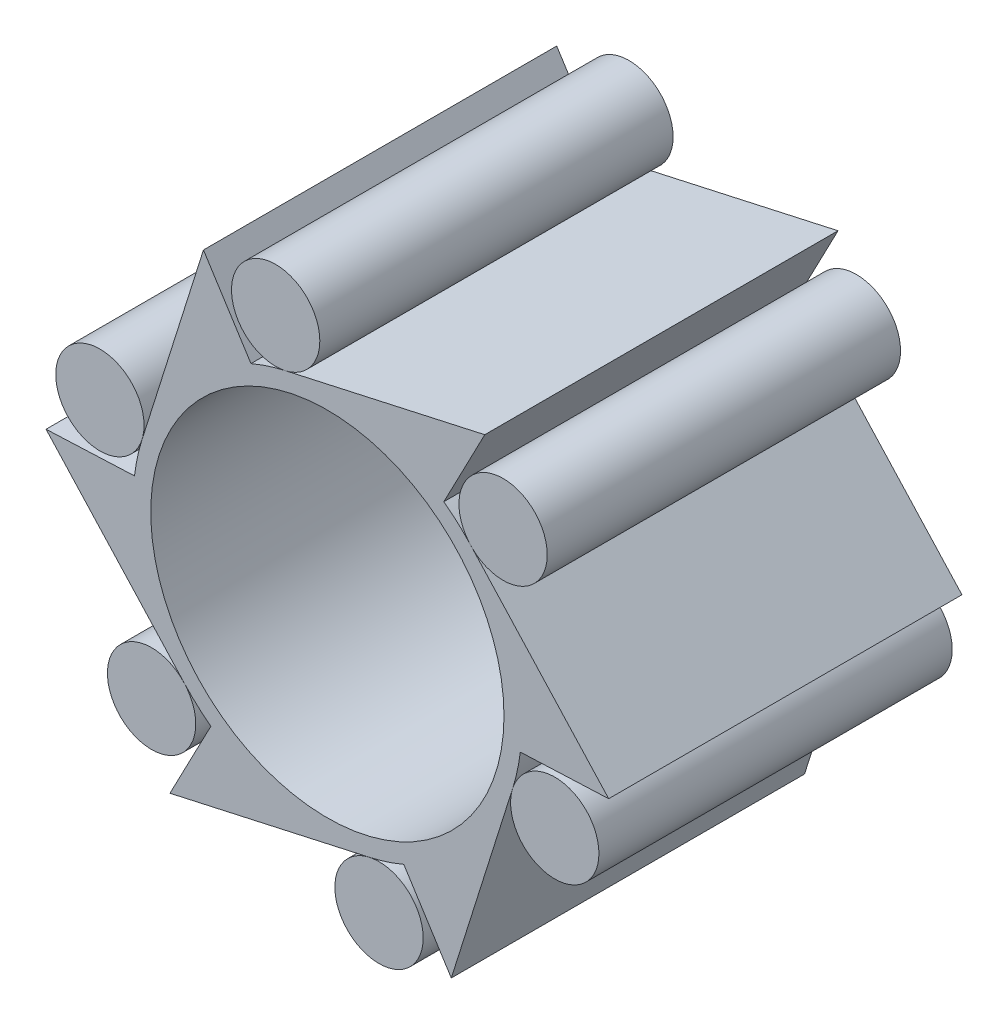
SolidWorks part; units mm, degrees
ref_plane "Front Plane" through (0, 0, 0) normal (0, 0, 1) x (1, 0, 0)
ref_plane "Top Plane" through (0, 0, 0) normal (0, 1, 0) x (1, 0, 0)
ref_plane "Right Plane" through (0, 0, 0) normal (1, 0, 0) x (0, 0, -1)
sketch "Sketch1" plane through (0, 0, 0) normal (0, 0, 1) x (1, 0, 0)
  line L0 (-1.1919, 5.3693) -> (4.4558, 6.623)
  line L1 (4.4558, 6.623) -> (3.2977, 4.4017)
  line L2 (4.054, 3.7169) -> (7.9636, -0.5474)
  line L3 (7.9636, -0.5474) -> (5.4609, -0.6551)
  line L4 (5.2459, -1.6524) -> (3.5078, -7.1704)
  line L5 (3.5078, -7.1704) -> (2.1631, -5.0568)
  line L6 (1.1919, -5.3693) -> (-4.4558, -6.623)
  line L7 (-4.4558, -6.623) -> (-3.2977, -4.4017)
  line L8 (-4.054, -3.7169) -> (-7.9636, 0.5474)
  line L9 (-7.9636, 0.5474) -> (-5.4609, 0.6551)
  line L12 (-5.2459, 1.6524) -> (-3.5078, 7.1704)
  line L13 (-3.5078, 7.1704) -> (-2.1631, 5.0568)
  circle A0 centre (0, 0) radius 5
  circle A1 centre (0, 0) radius 5.5
  circle A2 centre (0, 0) radius 8.0064
  dimension "D1" = 6
extrude "Boss-Extrude1" add sketch "Sketch1" along normal blind 10 contours A1 L9 L8 | A1 L13 L12 | A1 L7 L6 | A1 A0 | A1 L5 L4 | A1 L3 L2 | A1 L1 L0
sketch "Sketch4" plane through (0, 0, 10) normal (0, 0, 1) x (1, 0, 0)
  circle A1 centre (-1.4628, 6.5896) radius 1.25
  circle A2 centre (4.9753, 4.5616) radius 1.25
  circle A3 centre (6.4382, -2.028) radius 1.25
  circle A4 centre (1.4628, -6.5896) radius 1.25
  circle A5 centre (-4.9753, -4.5616) radius 1.25
  circle A6 centre (-6.4382, 2.028) radius 1.25
  dimension "D1" = 6
extrude "Boss-Extrude3" add sketch "Sketch4" along normal blind 0.001 and the other way blind 10 separate body
